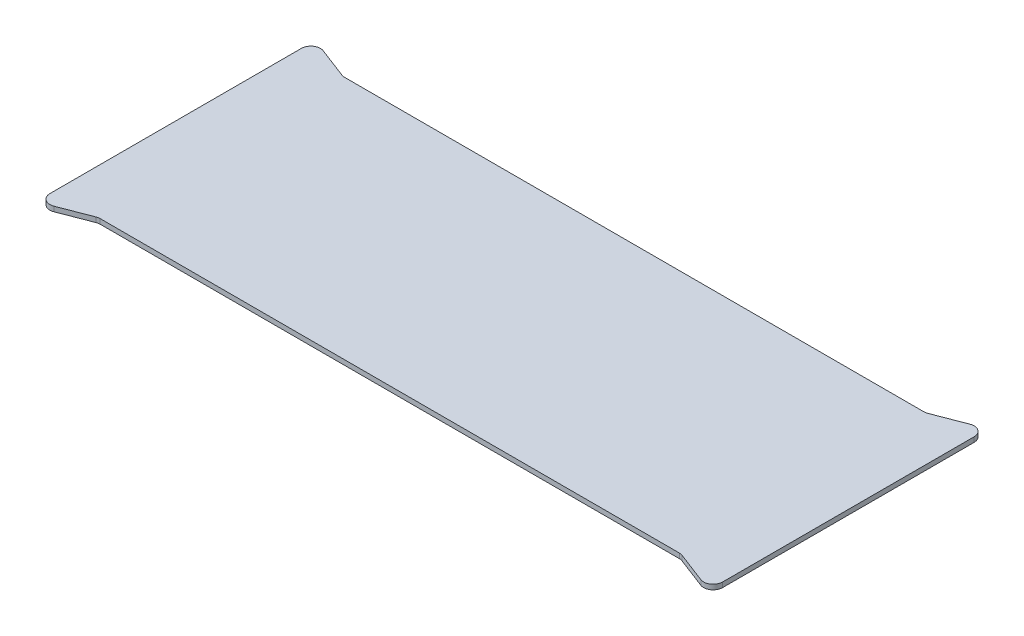
SolidWorks part; units mm, degrees
ref_plane "Front Plane" through (0, 0, 0) normal (0, 0, 1) x (1, 0, 0)
ref_plane "Top Plane" through (0, 0, 0) normal (0, 1, 0) x (1, 0, 0)
ref_plane "Right Plane" through (0, 0, 0) normal (1, 0, 0) x (0, 0, -1)
sketch "Sketch1" plane through (0, 0, 0) normal (0, 1, 0) x (1, 0, 0)
  line L0 (412.75, 0) -> (0, 158.75) construction
  line L1 (0, 0) -> (412.75, 0)
  line L3 (0, 158.75) -> (412.75, 158.75)
  line L4 (412.75, 0) -> (412.75, 158.75)
  line L5 (-3.5561, 166.7512) -> (17.247, 158.75)
  line L6 (0, 158.75) -> (0, 0)
  line L7 (-11.9699, 160.9725) -> (-11.9699, -2.2225)
  line L8 (416.3061, -8.0012) -> (395.503, 0)
  line L9 (424.7199, -2.2225) -> (424.7199, 160.9725)
  line L10 (416.3061, 166.7512) -> (395.503, 158.75)
  line L14 (-3.5561, -8.0012) -> (17.247, 0)
  line L15 (0, 0) -> (412.75, 158.75) construction
  circle A0 centre (418.5286, -2.2225) radius 6.1913
  circle A1 centre (418.5286, 160.9725) radius 6.1913
  circle A2 centre (-5.7786, 160.9725) radius 6.1913
  circle A3 centre (-5.7786, -2.2225) radius 6.1913
  dimension "D1" = 412.75
  dimension "D2" = 158.75
extrude "Boss-Extrude1" add sketch "Sketch1" along normal blind 3.175
fillet "Fillet1" radius 6.35 4 edges at (17.247, 1.5875, 0) (17.247, 1.5875, -158.75) (395.503, 1.5875, -158.75) (395.503, 1.5875, 0)
